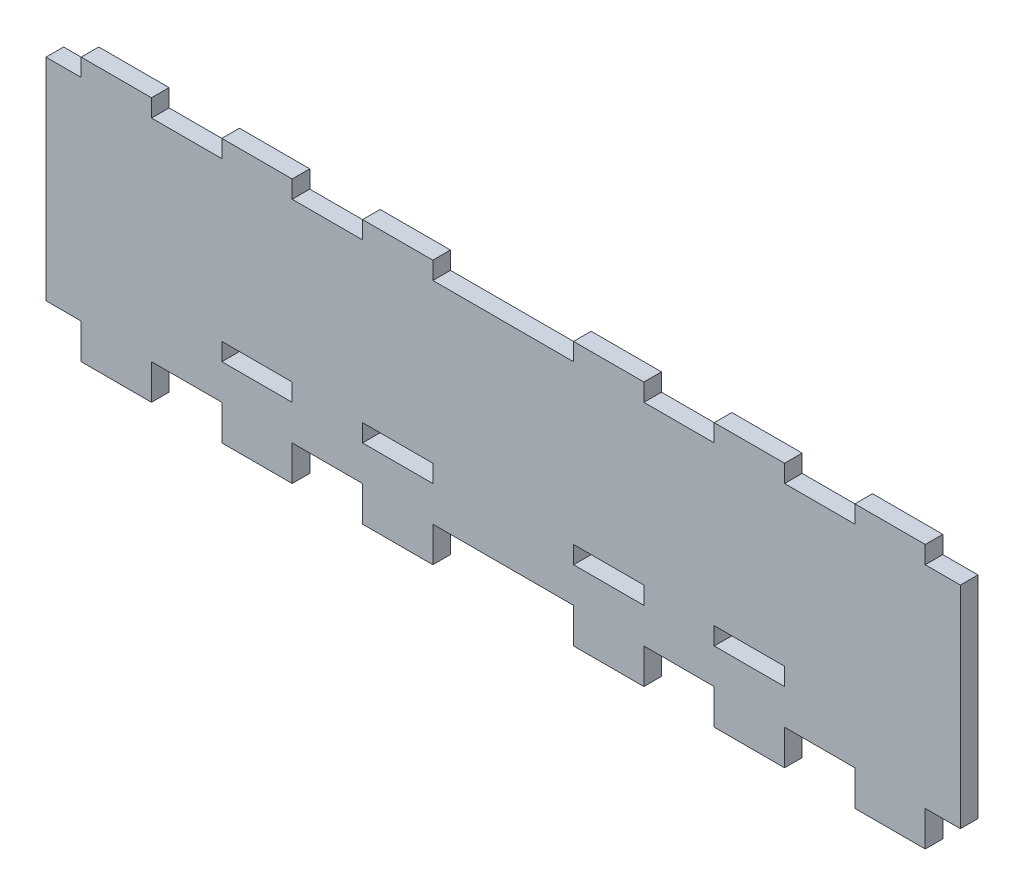
SolidWorks part; units mm, degrees
material "Beech"
ref_plane "Front" through (0, 0, 0) normal (0, 0, 1) x (1, 0, 0)
ref_plane "Top" through (0, 0, 0) normal (0, 1, 0) x (1, 0, 0)
ref_plane "Right" through (0, 0, 0) normal (1, 0, 0) x (0, 0, -1)
sketch "Sketch1" plane through (0, 0, 0) normal (0, 0, 1) x (1, 0, 0)
  line L0 (65, -13.75) -> (60, -13.75)
  line L1 (-65, -18.75) -> (65, -18.75) construction
  line L2 (-65, -18.75) -> (-65, 18.75) construction
  line L3 (-65, 18.75) -> (65, 18.75) construction
  line L4 (65, -18.75) -> (65, 18.75) construction
  line L5 (-65, -18.75) -> (65, 18.75) construction
  line L6 (-65, 18.75) -> (65, -18.75) construction
  line L7 (60, -13.75) -> (60, -18.75)
  line L8 (60, -18.75) -> (50, -18.75)
  line L9 (50, -18.75) -> (50, -13.75)
  line L10 (50, -13.75) -> (40, -13.75)
  line L11 (40, -13.75) -> (40, -18.75)
  line L12 (40, -18.75) -> (30, -18.75)
  line L13 (30, -18.75) -> (30, -13.75)
  line L14 (30, -13.75) -> (20, -13.75)
  line L15 (20, -13.75) -> (20, -18.75)
  line L16 (20, -18.75) -> (10, -18.75)
  line L17 (10, -18.75) -> (10, -13.75)
  line L18 (10, -13.75) -> (-10, -13.75)
  line L19 (0, -2.7055) -> (0, 5.2538) construction
  line L20 (8.0968, 0) -> (-8.7227, 0) construction
  line L21 (-10, -18.75) -> (-10, -13.75)
  line L22 (-20, -18.75) -> (-10, -18.75)
  line L23 (-20, -13.75) -> (-20, -18.75)
  line L24 (-30, -13.75) -> (-20, -13.75)
  line L25 (-30, -18.75) -> (-30, -13.75)
  line L26 (-40, -18.75) -> (-30, -18.75)
  line L27 (-40, -13.75) -> (-40, -18.75)
  line L28 (-50, -13.75) -> (-40, -13.75)
  line L29 (-50, -18.75) -> (-50, -13.75)
  line L30 (-60, -18.75) -> (-50, -18.75)
  line L31 (-60, -13.75) -> (-60, -18.75)
  line L32 (-65, -13.75) -> (-60, -13.75)
  line L33 (-65, 16.25) -> (-60, 16.25)
  line L34 (-60, 16.25) -> (-60, 18.75)
  line L35 (-60, 18.75) -> (-50, 18.75)
  line L36 (-50, 18.75) -> (-50, 16.25)
  line L37 (-50, 16.25) -> (-40, 16.25)
  line L38 (-40, 16.25) -> (-40, 18.75)
  line L39 (-40, 18.75) -> (-30, 18.75)
  line L40 (-30, 18.75) -> (-30, 16.25)
  line L41 (-30, 16.25) -> (-20, 16.25)
  line L42 (-20, 16.25) -> (-20, 18.75)
  line L43 (-20, 18.75) -> (-10, 18.75)
  line L44 (-10, 18.75) -> (-10, 16.25)
  line L45 (10, 16.25) -> (-10, 16.25)
  line L46 (10, 18.75) -> (10, 16.25)
  line L47 (20, 18.75) -> (10, 18.75)
  line L48 (20, 16.25) -> (20, 18.75)
  line L49 (30, 16.25) -> (20, 16.25)
  line L50 (30, 18.75) -> (30, 16.25)
  line L51 (40, 18.75) -> (30, 18.75)
  line L52 (40, 16.25) -> (40, 18.75)
  line L53 (50, 16.25) -> (40, 16.25)
  line L54 (50, 18.75) -> (50, 16.25)
  line L55 (60, 18.75) -> (50, 18.75)
  line L56 (60, 16.25) -> (60, 18.75)
  line L57 (65, 16.25) -> (60, 16.25)
  line L58 (-65, 16.25) -> (-65, -13.75)
  line L59 (65, 16.25) -> (65, -13.75)
  line L60 (-20, -8.75) -> (-20, -6.25)
  line L61 (-40, -8.75) -> (-30, -8.75)
  line L62 (-40, -8.75) -> (-40, -6.25)
  line L63 (-40, -6.25) -> (-30, -6.25)
  line L64 (-30, -8.75) -> (-30, -6.25)
  line L65 (-40, -8.75) -> (-30, -6.25) construction
  line L66 (-40, -6.25) -> (-30, -8.75) construction
  line L67 (-20, -8.75) -> (-10, -8.75)
  line L68 (-10, -8.75) -> (-10, -6.25)
  line L69 (-20, -6.25) -> (-10, -6.25)
  line L70 (20, -8.75) -> (10, -8.75)
  line L71 (10, -8.75) -> (10, -6.25)
  line L72 (20, -6.25) -> (10, -6.25)
  line L73 (20, -8.75) -> (20, -6.25)
  line L74 (40, -6.25) -> (30, -6.25)
  line L75 (30, -8.75) -> (30, -6.25)
  line L76 (40, -8.75) -> (30, -8.75)
  line L77 (40, -8.75) -> (40, -6.25)
  point P0 (0, 0)
  point P9 (-35, -7.5)
  point P26 (0, -13.75)
  point P64 (0, 16.25)
  point P65 (0, 18.75)
  dimension "D1" = 37.5
  dimension "D2" = 130
  dimension "D3" = 5
  dimension "D4" = 10
  dimension "D5" = 10
  dimension "D6" = 5
  dimension "D7" = 5
  dimension "D9" = 10
  dimension "D8" = 2
extrude "Boss-Extrude1" add sketch "Sketch1" along normal blind 2.5 contours L59 L57 L56 L55 L54 L53 L52 L51 L50 L49 L48 L47 L46 L45 L44 L43 L42 L41 L40 L39 L38 L37 L36 L35 L34 L33 L58 L32 L31 L30 L29 L28 L27 L26 L25 L24 L23 L22 L21 L18 L17 L16 L15 L14 L13 L12 L11 L10 L9 L8 L7
